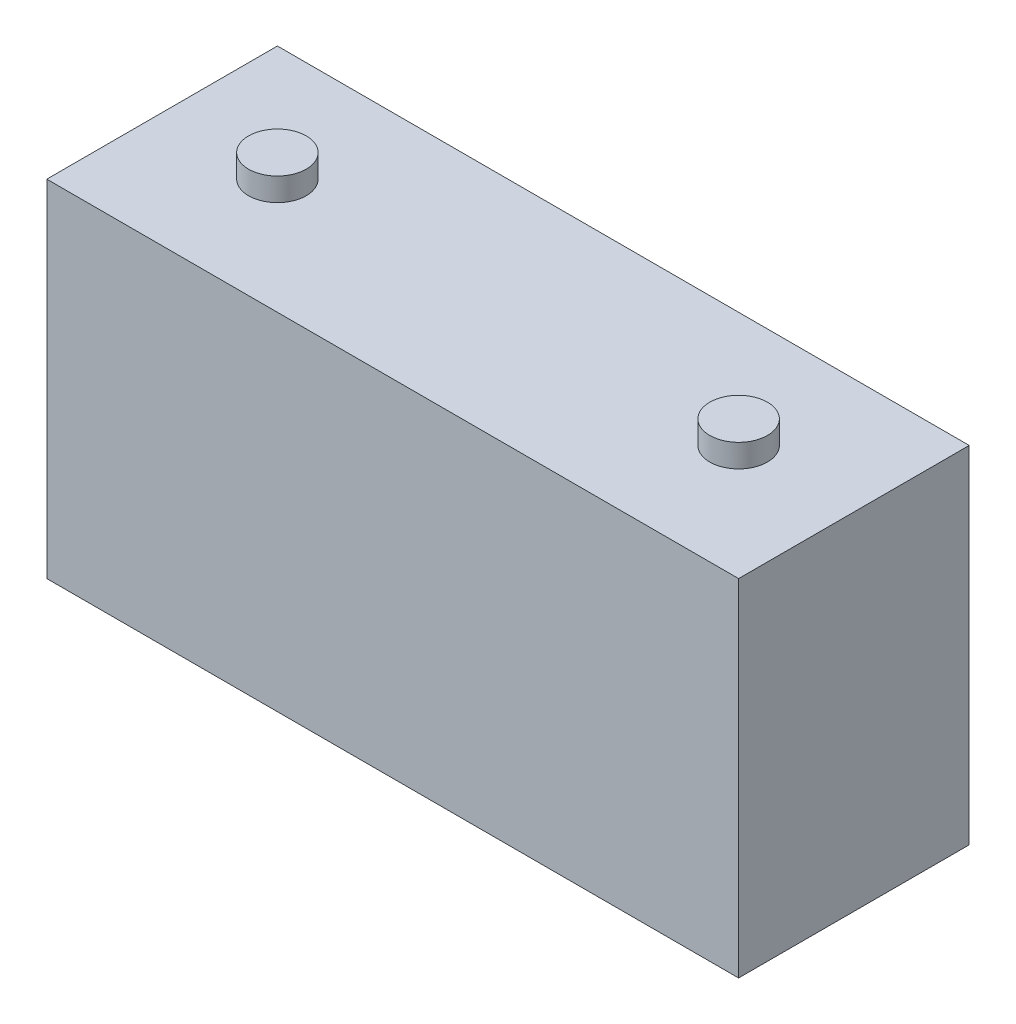
SolidWorks part; units mm, degrees
ref_plane "前视基准面" through (0, 0, 0) normal (0, 0, 1) x (1, 0, 0)
ref_plane "上视基准面" through (0, 0, 0) normal (0, 1, 0) x (1, 0, 0)
ref_plane "右视基准面" through (0, 0, 0) normal (1, 0, 0) x (0, 0, -1)
sketch "草图1" plane through (0, 0, 0) normal (0, 0, 1) x (1, 0, 0)
  line L1 (-300, -150) -> (300, -150)
  line L2 (-300, -150) -> (-300, 150)
  line L3 (-300, 150) -> (300, 150)
  line L4 (300, -150) -> (300, 150)
  line L5 (-300, -150) -> (300, 150) construction
  line L6 (-300, 150) -> (300, -150) construction
  point P0 (0, 0)
  dimension "D1" = 600
  dimension "D2" = 300
extrude "凸台-拉伸1" add sketch "草图1" along normal blind 200
sketch "草图2" plane through (0, -150, 0) normal (0, -1, 0) x (1, 0, 0)
  line L0 (-300, 200) -> (-300, 0) construction
  line L1 (300, 200) -> (300, 0) construction
  circle A0 centre (-200, 100) radius 25
  circle A1 centre (200, 100) radius 25
  dimension "D1" = 50
  dimension "D4" = 50
  dimension "D2" = 100
  dimension "D3" = 100
extrude "凸台-拉伸2" add sketch "草图2" along normal blind 20
sketch "草图3" plane through (0, 150, 0) normal (0, 1, 0) x (1, 0, 0)
  line L0 (300, -100) -> (-300, -100) construction
  line L1 (300, -200) -> (300, 0) construction
  line L2 (-300, -200) -> (-300, 0) construction
  circle A0 centre (200, -100) radius 25
  circle A1 centre (-200, -100) radius 25
  dimension "D1" = 50
  dimension "D2" = 100
  dimension "D3" = 50
  dimension "D4" = 100
extrude "凸台-拉伸3" add sketch "草图3" along normal blind 20
